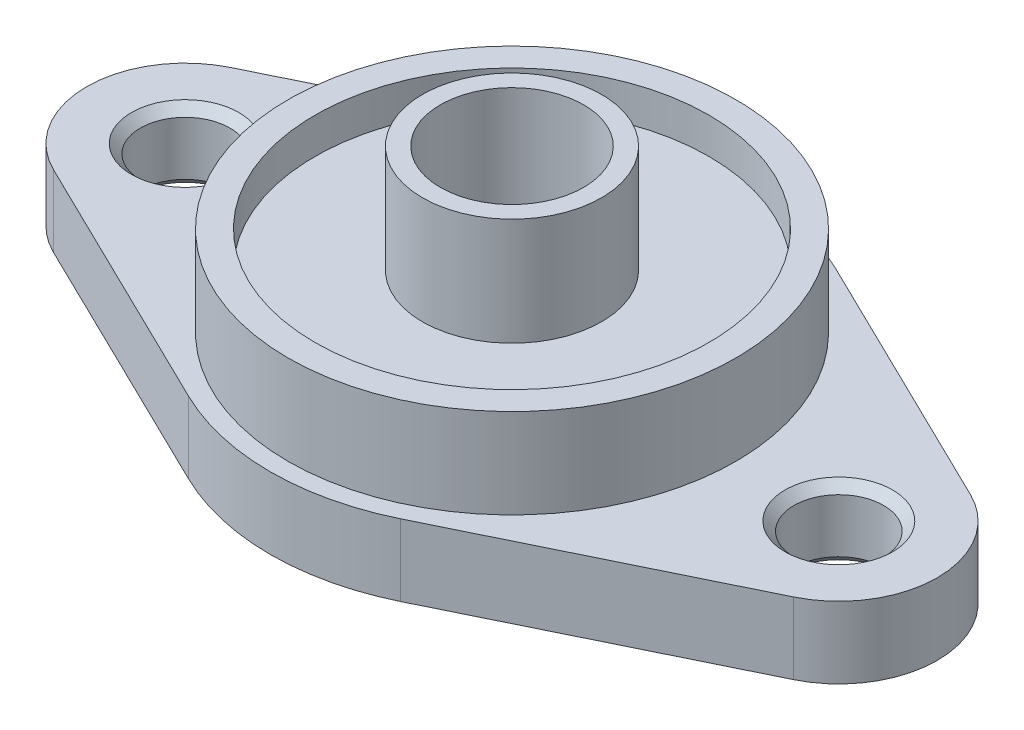
SolidWorks part; units mm, degrees
ref_plane "Alzado" through (0, 0, 0) normal (0, 0, 1) x (1, 0, 0)
ref_plane "Planta" through (0, 0, 0) normal (0, 1, 0) x (1, 0, 0)
ref_plane "Vista lateral" through (0, 0, 0) normal (1, 0, 0) x (0, 0, -1)
sketch "Croquis1" plane through (0, 0, 0) normal (0, 1, 0) x (1, 0, 0)
  line L0 (-18.25, 0) -> (-15.75, 0) construction
  line L1 (-5.9178, 12.1338) -> (-20.661, 4.9434)
  line L2 (-5.9178, -12.1338) -> (-20.661, -4.9434)
  line L3 (0, 0) -> (0, 7.3919) construction
  line L4 (5.9178, -12.1338) -> (20.661, -4.9434)
  line L5 (5.9178, 12.1338) -> (20.661, 4.9434)
  line L6 (-13.5, 0) -> (4, 0) construction
  line L7 (12.75, 0) -> (18.25, 0) construction
  circle A0 centre (0, 0) radius 4
  arc A1 (-5.9178, -12.1338) -> (5.9178, -12.1338) centre (0, 0) ccw
  circle A2 centre (-18.25, 0) radius 2.5
  circle A3 centre (18.25, 0) radius 2.5
  arc A4 (-20.661, 4.9434) -> (-20.661, -4.9434) centre (-18.25, 0) ccw
  arc A5 (20.661, -4.9434) -> (20.661, 4.9434) centre (18.25, 0) ccw
  arc A6 (5.9178, 12.1338) -> (-5.9178, 12.1338) centre (0, 0) ccw
  dimension "D1" = 8
  dimension "D2" = 27
  dimension "D4" = 5
  dimension "D5" = 5
  dimension "D6" = 11
  dimension "D7" = 11
  dimension "D3" = 36.5
extrude "Saliente-Extruir1" add sketch "Croquis1" along normal blind 4
sketch "Croquis2" plane through (0, 4, 0) normal (0, 1, 0) x (1, 0, 0)
  circle A0 centre (0, 0) radius 5
  circle A1 centre (0, 0) radius 4 construction
  circle A2 centre (0, 0) radius 4
  dimension "D1" = 10
extrude "Saliente-Extruir2" add sketch "Croquis2" along normal blind 9
sketch "Croquis3" plane through (0, 4, 0) normal (0, 1, 0) x (1, 0, 0)
  circle A0 centre (0, 0) radius 12.5
  circle A1 centre (0, 0) radius 11
  dimension "D1" = 25
  dimension "D2" = 22
extrude "Saliente-Extruir3" add sketch "Croquis3" along normal blind 5
sketch "Croquis5" plane through (0, 4, 0) normal (0, 1, 0) x (1, 0, 0)
  circle A0 centre (0, 0) radius 5 construction
  circle A1 centre (0, 0) radius 11
  circle A2 centre (0, 0) radius 11
  circle A3 centre (0, 0) radius 5
  dimension "D1" = 0
extrude "Saliente-Extruir4" add sketch "Croquis5" along normal blind 3
chamfer "Chaflán1" distance 0.5 angle 45 4 edges at (18.25, 0, 2.5) (18.25, 4, 2.5) (-18.25, 0, 2.5) (-18.25, 4, 2.5)
